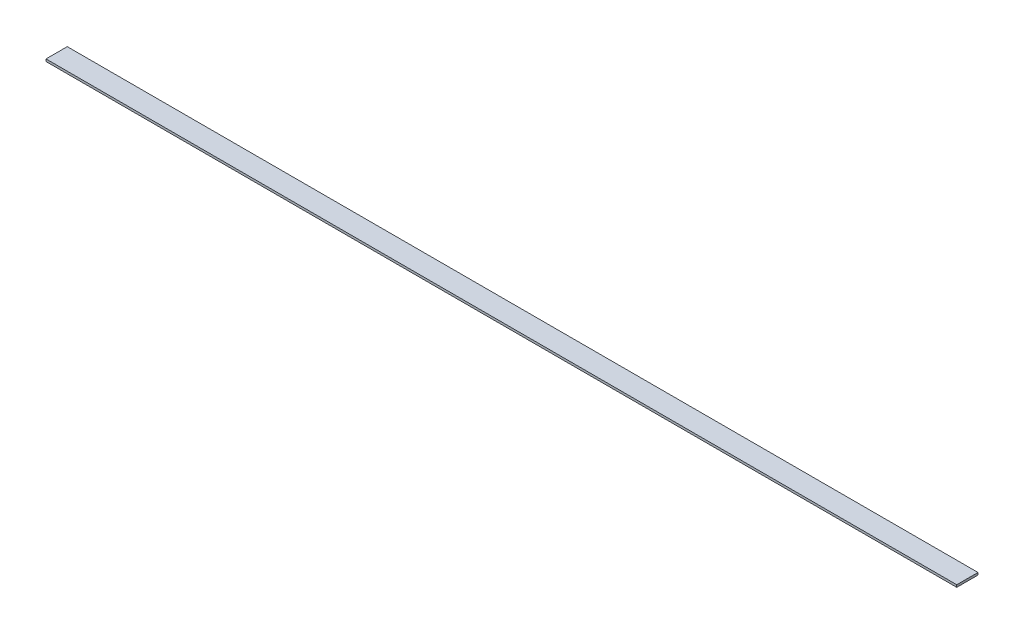
SolidWorks part; units mm, degrees
ref_plane "Спереди" through (0, 0, 0) normal (0, 0, 1) x (1, 0, 0)
ref_plane "Сверху" through (0, 0, 0) normal (0, 1, 0) x (1, 0, 0)
ref_plane "Справа" through (0, 0, 0) normal (1, 0, 0) x (0, 0, -1)
sketch "Эскиз1" plane through (0, 0, 0) normal (0, 1, 0) x (1, 0, 0)
  line L1 (0, 0) -> (300, 0)
  line L2 (0, 0) -> (0, 7)
  line L3 (0, 7) -> (300, 7)
  line L4 (300, 0) -> (300, 7)
  dimension "D1" = 7
  dimension "D2" = 300
extrude "Бобышка-Вытянуть1" add sketch "Эскиз1" along normal blind 0.75
